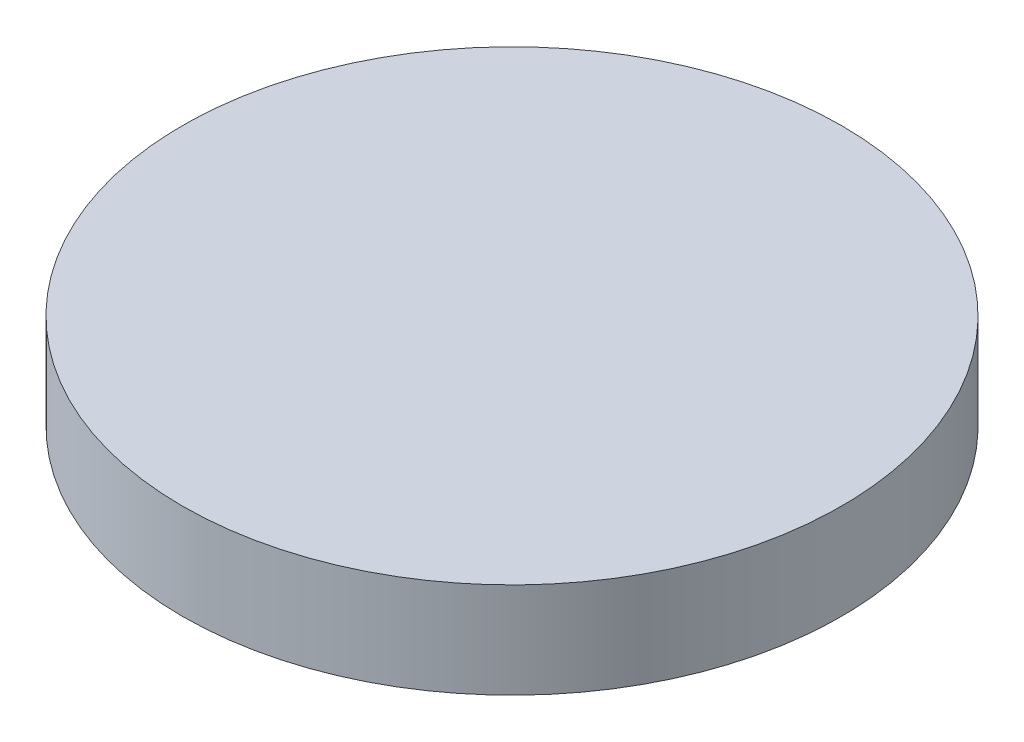
SolidWorks part; units mm, degrees
material "PTFE (general)"
ref_plane "Front Plane" through (0, 0, 0) normal (0, 0, 1) x (1, 0, 0)
ref_plane "Top Plane" through (0, 0, 0) normal (0, 1, 0) x (1, 0, 0)
ref_plane "Right Plane" through (0, 0, 0) normal (1, 0, 0) x (0, 0, -1)
sketch "Sketch1" plane through (0, 0, 0) normal (0, 1, 0) x (1, 0, 0)
  circle A0 centre (0, 0) radius 6.9
  dimension "D1" = 13.8
extrude "Boss-Extrude1" add sketch "Sketch1" along normal blind 2
